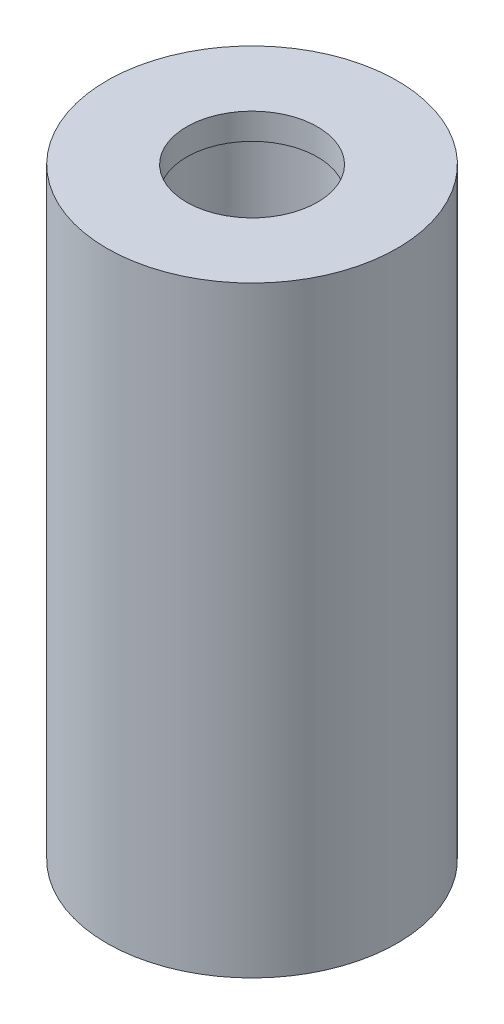
SolidWorks part; units mm, degrees
ref_plane "前视基准面" through (0, 0, 0) normal (0, 0, 1) x (1, 0, 0)
ref_plane "上视基准面" through (0, 0, 0) normal (0, 1, 0) x (1, 0, 0)
ref_plane "右视基准面" through (0, 0, 0) normal (1, 0, 0) x (0, 0, -1)
other "Configuration Table"
sketch "草图1" plane through (0, 0, 0) normal (0, 1, 0) x (1, 0, 0)
  circle A0 centre (0, 0) radius 2.55
  circle A1 centre (0, 0) radius 5.55
  dimension "D1" = 5.1
  dimension "D2" = 3
extrude "凸台-拉伸1" add sketch "草图1" along normal blind 23
sketch "草图2" plane through (0, 23, 0) normal (0, 1, 0) x (1, 0, 0)
  circle A0 centre (0, 0) radius 2.5
  circle A1 centre (0, 0) radius 2.55
  dimension "D1" = 5
extrude "凸台-拉伸2" add sketch "草图2" against normal blind 1
